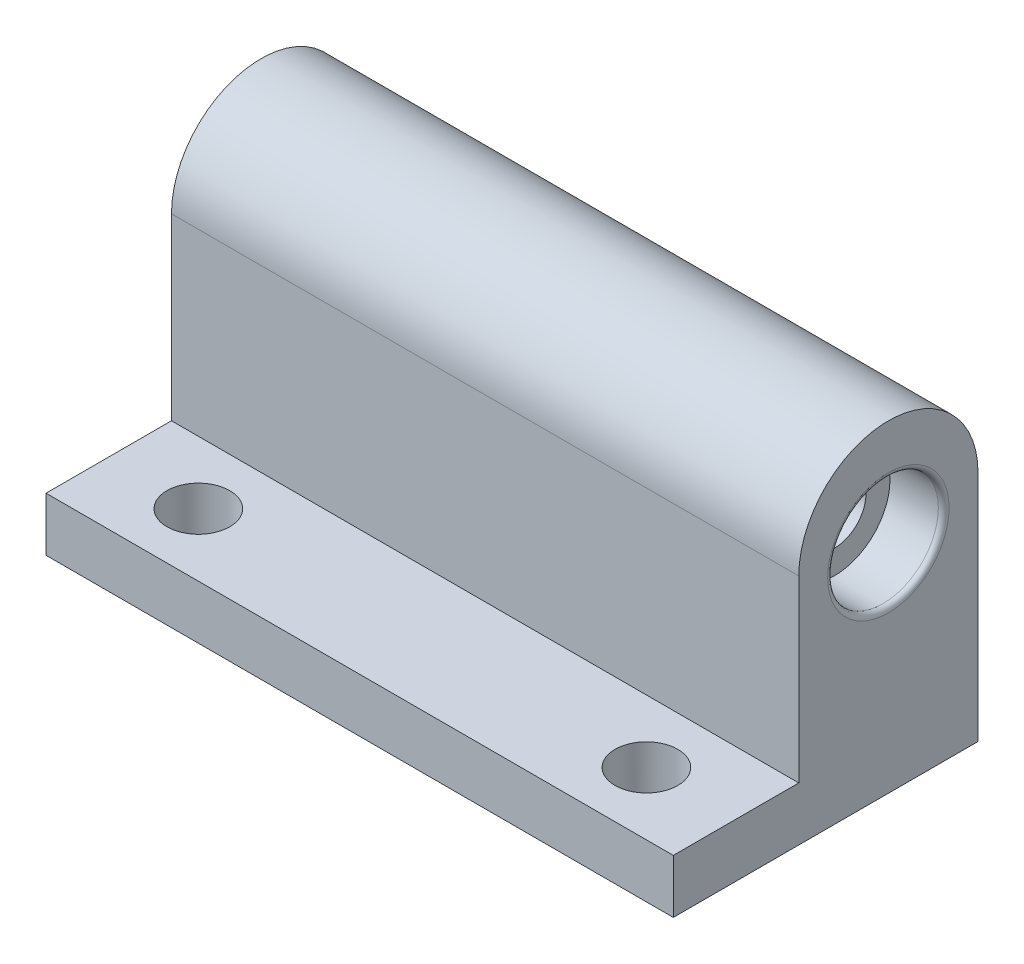
SolidWorks part; units mm, degrees
ref_plane "Front Plane" through (0, 0, 0) normal (0, 0, 1) x (1, 0, 0)
ref_plane "Top Plane" through (0, 0, 0) normal (0, 1, 0) x (1, 0, 0)
ref_plane "Right Plane" through (0, 0, 0) normal (1, 0, 0) x (0, 0, -1)
sketch "Sketch1" plane through (0, 0, 0) normal (0, 1, 0) x (1, 0, 0)
  line L1 (-17.5, 15) -> (17.5, 15)
  line L2 (-17.5, 15) -> (-17.5, -15)
  line L3 (-17.5, -15) -> (17.5, -15)
  line L4 (17.5, 15) -> (17.5, -15)
  line L5 (-17.5, 15) -> (17.5, -15) construction
  line L6 (-17.5, -15) -> (17.5, 15) construction
  point P0 (0, 0)
  dimension "D1" = 35
  dimension "D2" = 30
extrude "Boss-Extrude1" add sketch "Sketch1" along normal blind 22.1
sketch "Sketch2" plane through (17.5, 0, 0) normal (1, 0, 0) x (0, 0, -1)
  line L0 (0, 12.155) -> (0, -12.155) construction
  line L1 (-15, 22.1) -> (15, 22.1) construction
  circle A0 centre (0, 12.1) radius 3.0875
  dimension "D1" = 6.175
  dimension "D2" = 10
extrude "Cut-Extrude1" cut sketch "Sketch2" against normal blind 3
sketch "Sketch3" plane through (14.5, 0, 0) normal (1, 0, 0) x (0, 0, -1)
  circle A0 centre (0, 12.1) radius 1.75
  dimension "D1" = 3.5
extrude "Cut-Extrude2" cut sketch "Sketch3" against normal through all
sketch "Sketch4" plane through (-17.5, 0, 0) normal (-1, 0, 0) x (0, 0, 1)
  circle A0 centre (0, 12.1) radius 3.0875
  dimension "D1" = 6.175
extrude "Cut-Extrude3" cut sketch "Sketch4" against normal blind 3
sketch "Sketch5" plane through (0, 22.1, 0) normal (0, 1, 0) x (1, 0, 0)
  line L0 (-17.5, 15) -> (-17.5, -15) construction
  line L1 (17.5, 15) -> (-17.5, 15) construction
  line L2 (-17.5, -15) -> (17.5, -15) construction
  line L3 (17.5, -15) -> (17.5, 15) construction
  circle A0 centre (-12.5, 8.5) radius 1.75
  circle A1 centre (12.5, 8.5) radius 1.75
  circle A2 centre (12.5, -8.5) radius 1.75
  circle A3 centre (-12.5, -8.5) radius 1.75
  dimension "D5" = 3.5
  dimension "D1" = 5
  dimension "D2" = 6.5
  dimension "D3" = 6.5
  dimension "D4" = 5
extrude "Cut-Extrude4" cut sketch "Sketch5" against normal through all
sketch "Sketch6" plane through (-17.5, 0, 0) normal (-1, 0, 0) x (0, 0, 1)
  line L0 (0, 0) -> (0, 3) construction
  line L1 (0, -12.155) -> (0, 12.155) construction
  line L2 (-15, 3) -> (-5, 3) construction
  line L3 (-15, 22.1) -> (-15, 0) construction
  line L4 (-5, 3) -> (-5, 13)
  line L5 (5, 13) -> (5, 3)
  line L6 (5, 3) -> (15, 3)
  line L7 (15, 22.1) -> (15, 0) construction
  line L8 (-15, 3) -> (-15, 22.1)
  line L9 (-15, 22.1) -> (15, 22.1)
  line L10 (15, 22.1) -> (15, 3)
  line L11 (-5, 3) -> (-5, 0)
  line L12 (16.5, 0) -> (-16.5, 0) construction
  line L13 (-5, 0) -> (-15, 0)
  line L14 (-15, 0) -> (-15, 3)
  arc A0 (-5, 13) -> (5, 13) centre (0, 13) cw
  point P17 (0, 18)
  dimension "D4" = 18
  dimension "D1" = 3
  dimension "D2" = 10
  dimension "D3" = 10
extrude "Cut-Extrude5" cut sketch "Sketch6" against normal through all
fillet "Fillet1" radius 0.3 2 edges at (17.5, 12.1, -3.0875) (-17.5, 12.1, 3.0875)
sketch "Sketch7" plane through (0, 3, 0) normal (0, 1, 0) x (1, 0, 0)
  line L0 (-17.5, -12) -> (17.5, -12)
  line L1 (-17.5, -5) -> (-17.5, -15) construction
  line L2 (17.5, -5) -> (17.5, -15) construction
  line L3 (17.5, -12) -> (17.5, -15)
  line L4 (17.5, -15) -> (-17.5, -15)
  line L5 (-17.5, -15) -> (-17.5, -12)
  dimension "D1" = 3
extrude "Cut-Extrude6" cut sketch "Sketch7" against normal blind 10
